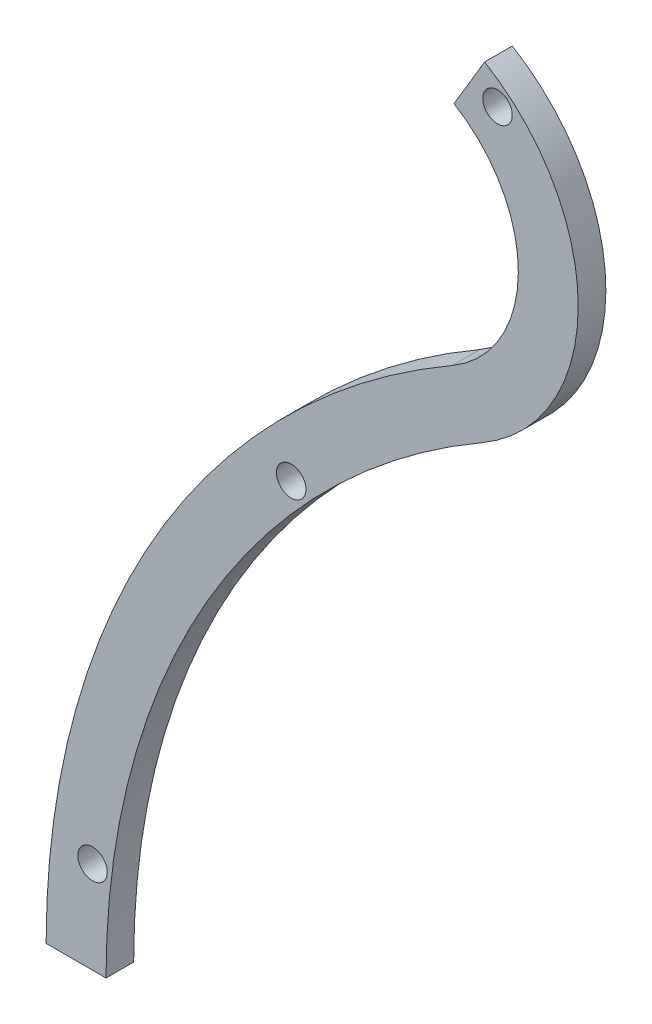
SolidWorks part; units mm, degrees
material "Thornel Mat VMA"
ref_plane "Front Plane" through (0, 0, 0) normal (0, 0, 1) x (1, 0, 0)
ref_plane "Top Plane" through (0, 0, 0) normal (0, 1, 0) x (1, 0, 0)
ref_plane "Right Plane" through (0, 0, 0) normal (1, 0, 0) x (0, 0, -1)
sketch "Sketch1" plane through (0, 0, 0) normal (0, 0, 1) x (1, 0, 0)
  line L0 (-34.9342, 0) -> (-22.9342, 0) construction
  line L1 (-36.9342, 0) -> (-30.4342, 0)
  line L2 (7.3248, 101.0489) -> (10.6521, 106.6327)
  arc A0 (10.6521, 106.6327) -> (10.4047, 70.735) centre (0, 88.7564) cw
  arc A1 (10.4047, 70.735) -> (-30.4342, 0) centre (51.2436, 0) ccw
  arc A2 (7.3248, 101.0489) -> (7.1547, 76.3642) centre (0, 88.7564) cw
  arc A3 (7.1547, 76.3642) -> (-36.9342, 0) centre (51.2436, 0) ccw
  arc A6 (8.1547, 74.6321) -> (1.4591, 105.0004) centre (0, 88.7564) ccw construction
  arc A7 (8.1547, 74.6321) -> (-34.9342, 0) centre (51.2436, 0) ccw construction
  circle A8 centre (12.0481, 103.1148) radius 1.6 construction
  circle A9 centre (12.0481, 103.1148) radius 1.6
  circle A10 centre (-10.3376, 56.7516) radius 1.6
  circle A11 centre (-31.9008, 10) radius 1.6
  point P12 (0, 88.7564)
  dimension "D1" = 4.5
  dimension "D2" = 2
  dimension "D3" = 3
  dimension "D4" = 3.2
extrude "Boss-Extrude1" add sketch "Sketch1" along normal blind 3
